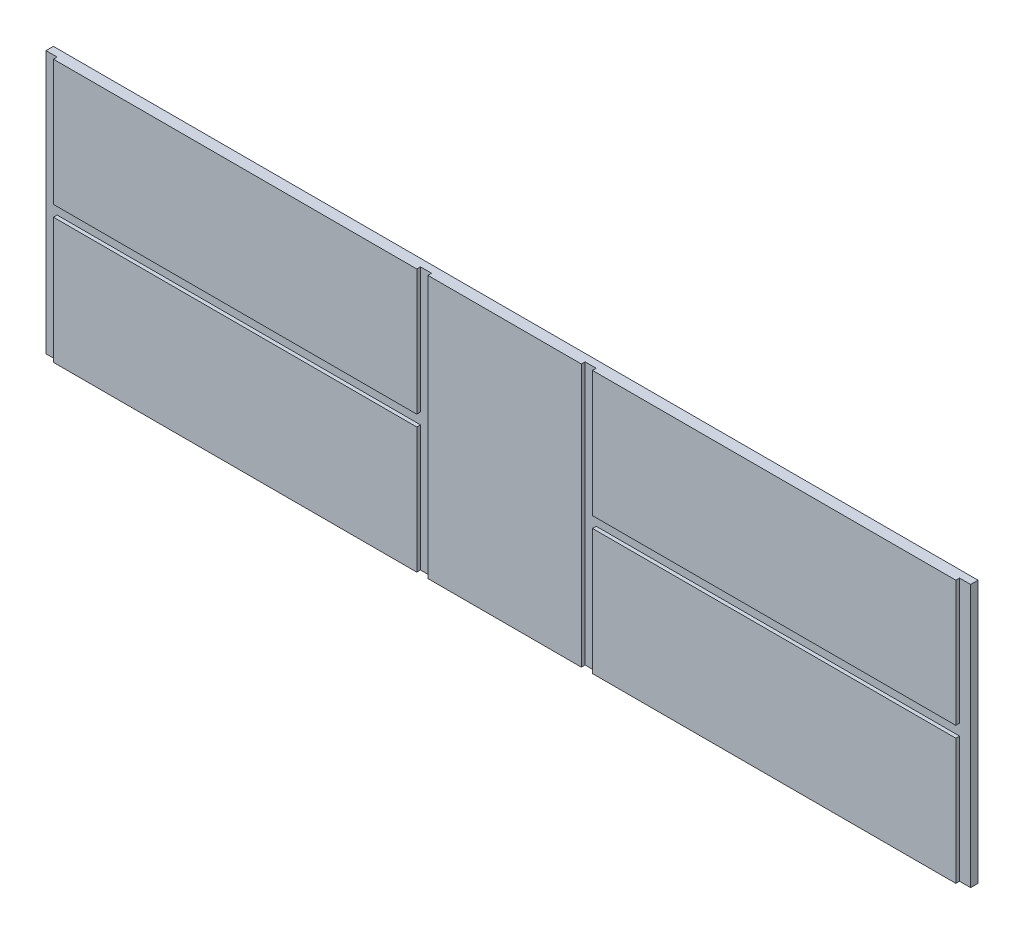
SolidWorks part; units mm, degrees
material "Pine"
ref_plane "Front Plane" through (0, 0, 0) normal (0, 0, 1) x (1, 0, 0)
ref_plane "Top Plane" through (0, 0, 0) normal (0, 1, 0) x (1, 0, 0)
ref_plane "Right Plane" through (0, 0, 0) normal (1, 0, 0) x (0, 0, -1)
sketch "Panel" plane through (0, 0, 0) normal (0, 0, 1) x (1, 0, 0)
  line L6 (0, 0) -> (1000, 0)
  line L10 (0, 0) -> (0, 284)
  line L11 (0, 284) -> (1000, 284)
  line L12 (1000, 0) -> (1000, 284)
  dimension "D1" = 1000
  dimension "width" = 284
extrude "Panel Ply" add sketch "Panel" along normal blind 12
sketch "Sketch2" plane through (0, 0, 12) normal (0, 0, 1) x (1, 0, 0)
  line L0 (0, 0) -> (1000, 0) construction
  line L1 (0, 284) -> (12, 284)
  line L2 (0, 284) -> (0, 0)
  line L3 (0, 0) -> (12, 0)
  line L4 (12, 284) -> (12, 0)
  line L5 (0, 284) -> (1000, 284) construction
  line L6 (1000, 284) -> (988, 284)
  line L7 (1000, 284) -> (1000, 0)
  line L8 (1000, 0) -> (988, 0)
  line L9 (988, 284) -> (988, 0)
  line L10 (405, 284) -> (417, 284)
  line L11 (405, 284) -> (405, 0)
  line L12 (405, 0) -> (417, 0)
  line L13 (417, 284) -> (417, 0)
  line L15 (583, 284) -> (595, 284)
  line L16 (583, 284) -> (583, 0)
  line L17 (583, 0) -> (595, 0)
  line L18 (595, 284) -> (595, 0)
  dimension "D1" = 12
  dimension "D2" = 12
  dimension "D3" = 12
  dimension "D4" = 12
  dimension "D5" = 393
  dimension "D6" = 393
extrude "Vertical Housing Cut" cut sketch "Sketch2" against normal blind 4
sketch "Sketch3" plane through (0, 0, 12) normal (0, 0, 1) x (1, 0, 0)
  line L0 (12, 0) -> (12, 284) construction
  line L1 (12, 148) -> (405, 148)
  line L2 (12, 148) -> (12, 136)
  line L3 (12, 136) -> (405, 136)
  line L4 (405, 148) -> (405, 136)
  line L5 (405, 284) -> (405, 0) construction
  line L6 (595, 0) -> (595, 284) construction
  line L7 (595, 148) -> (988, 148)
  line L8 (595, 148) -> (595, 136)
  line L9 (595, 136) -> (988, 136)
  line L10 (988, 148) -> (988, 136)
  line L11 (988, 284) -> (988, 0) construction
  line L12 (0, 284) -> (1000, 284) construction
  dimension "D1" = 12
  dimension "D2" = 12
  dimension "offset" = 136
  dimension "D3" = 136
extrude "Horizontal Housing Cut" cut sketch "Sketch3" against normal blind 4
equation "\"LENGTH\" = 1000mm"
equation "\"PLY\"= 12mm"
equation "\"D1@Panel\" = \"LENGTH\""
equation "\"D1@Panel Ply\" = \"PLY\""
equation "\"WIDTH\" = 300mm"
equation "\"HEIGHT\" = 300mm"
equation "\"HOUSING_DEPTH\" = 4mm"
equation "\"CENTER_BRACE_LENGTH\" = 393mm"
equation "\"PANEL_WIDTH\"= \"LENGTH\" - \"CENTER_BRACE_LENGTH\" * 2 - \"PLY\" * 4"
equation "\"PANEL_SMALL_HEIGHT\" = 70mm"
equation "\"PORT_WIDTH\" = 90mm"
equation "\"PORT_RADIUS\" = 15mm"
equation "\"PORT_BRACE_HEIGHT\" = 92mm"
equation "\"DOWEL_SIZE\" = 0.25in"
equation "\"DOWEL_OFFSET\" = 30mm"
equation "\"width@Panel\" = \"WIDTH\" - \"PLY\" * 2 + \"HOUSING_DEPTH\" * 2"
equation "\"D1@Sketch2\"=\"PLY\""
equation "\"D2@Sketch2\"=\"PLY\""
equation "\"D1@Vertical Housing Cut\" = \"HOUSING_DEPTH\""
equation "\"D3@Sketch2\"=\"PLY\""
equation "\"D4@Sketch2\"=\"PLY\""
equation "\"D5@Sketch2\"=\"CENTER_BRACE_LENGTH\""
equation "\"D6@Sketch2\"=\"CENTER_BRACE_LENGTH\""
equation "\"D1@Sketch3\"=\"PLY\""
equation "\"D2@Sketch3\"=\"PLY\""
equation "\"offset@Sketch3\" = \"width@Panel\" / 2 - \"PLY\" / 2"
equation "\"D3@Sketch3\"=\"offset@Sketch3\""
equation "\"D1@Horizontal Housing Cut\"=\"HOUSING_DEPTH\""
